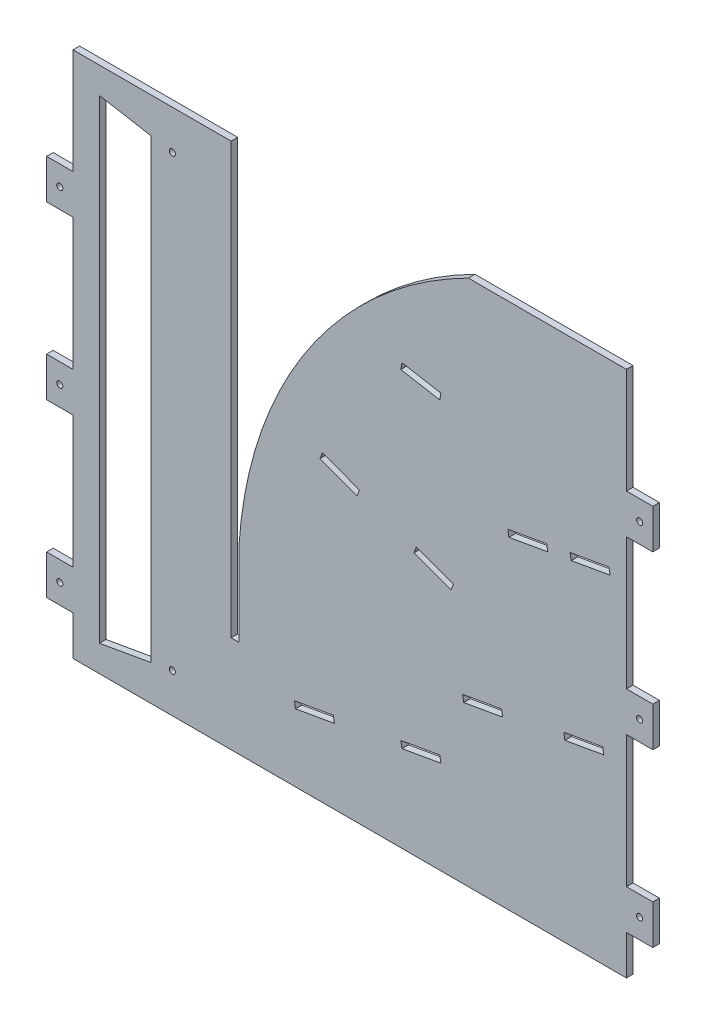
SolidWorks part; units mm, degrees
ref_plane "Front Plane" through (0, 0, 0) normal (0, 0, 1) x (1, 0, 0)
ref_plane "Top Plane" through (0, 0, 0) normal (0, 1, 0) x (1, 0, 0)
ref_plane "Right Plane" through (0, 0, 0) normal (1, 0, 0) x (0, 0, -1)
sketch "Sketch1" plane through (0, 0, 0) normal (0, 0, 1) x (1, 0, 0)
  line L0 (76.2, 254) -> (76.2, 46.7342)
  line L1 (190.5, 55.2817) -> (190.5, 254) construction
  line L2 (0, 0) -> (0, 19.05)
  line L3 (0, 254) -> (76.2, 254)
  line L5 (0, 203.2) -> (0, 254)
  line L6 (190.5, 254) -> (266.7, 254)
  line L7 (266.7, 254) -> (266.7, 203.2)
  line L8 (266.7, 0) -> (0, 0)
  line L9 (266.7, 203.2) -> (279.4, 203.2)
  line L10 (279.4, 203.2) -> (279.4, 184.15)
  line L11 (279.4, 184.15) -> (266.7, 184.15)
  line L12 (266.7, 184.15) -> (266.7, 120.65)
  line L13 (266.7, 120.65) -> (279.4, 120.65)
  line L14 (279.4, 120.65) -> (279.4, 101.6)
  line L15 (279.4, 101.6) -> (266.7, 101.6)
  line L16 (0, 203.2) -> (-12.7, 203.2)
  line L17 (0, 120.65) -> (0, 184.15)
  line L18 (0, 184.15) -> (-12.7, 184.15)
  line L19 (-12.7, 203.2) -> (-12.7, 184.15)
  line L20 (0, 120.65) -> (-12.7, 120.65)
  line L21 (0, 38.1) -> (0, 101.6)
  line L22 (0, 101.6) -> (-12.7, 101.6)
  line L23 (-12.7, 120.65) -> (-12.7, 101.6)
  line L24 (0, 38.1) -> (-12.7, 38.1)
  line L25 (266.7, 101.6) -> (266.7, 38.1)
  line L26 (0, 19.05) -> (-12.7, 19.05)
  line L27 (-12.7, 38.1) -> (-12.7, 19.05)
  line L28 (266.7, 38.1) -> (279.4, 38.1)
  line L29 (279.4, 38.1) -> (279.4, 19.05)
  line L30 (279.4, 19.05) -> (266.7, 19.05)
  line L31 (266.7, 19.05) -> (266.7, 0)
  line L33 (76.2, 46.7342) -> (80.01, 46.7342)
  line L34 (80.01, 46.7342) -> (80.01, 87.375)
  arc A0 (80.01, 87.375) -> (190.5, 254) centre (281.0737, 73.9943) cw
  dimension "D5" = 19.05
  dimension "D7" = 3.81
  dimension "D1" = 254
  dimension "D2" = 76.2
  dimension "D3" = 12.7
  dimension "D4" = 19.05
  dimension "D6" = 266.7
  dimension "D13" = 63.5
  dimension "D14" = 63.5
extrude "Boss-Extrude1" add sketch "Sketch1" along normal blind 3.175
sketch "Sketch4" [suppressed] plane through (0, 0, 3.175) normal (0, 0, 1) x (1, 0, 0)
  text T0 "Gravity Gizmo" font "Century Gothic" height in points 48
sketch "Sketch10" plane through (0, 0, 3.175) normal (0, 0, 1) x (1, 0, 0)
  line L0 (12.7, 12.7) -> (12.7, 241.3)
  line L1 (12.7, 12.7) -> (37.7141, 17.1107)
  line L2 (12.7, 241.3) -> (37.7141, 236.8893)
  line L3 (37.7141, 17.1107) -> (37.7141, 236.8893)
  line L4 (0, 19.05) -> (0, 0) construction
  line L5 (0, 0) -> (266.7, 0) construction
  line L6 (76.2, 254) -> (0, 254) construction
  point P3 (133.35, 0)
  dimension "D1" = 25.4
  dimension "D2" = 12.7
  dimension "D3" = 280
  dimension "D4" = 12.7
  dimension "D5" = 12.7
  dimension "D6" = 280
extrude "Cut-Extrude5" cut sketch "Sketch10" against normal through all
hole_wizard "#4 Clearance Hole1" positions "Sketch17" profile "Sketch16" hole size "#4" standard "ANSI Inch" end condition through all
sketch "Sketch17" plane through (0, 0, 3.175) normal (0, 0, 1) x (1, 0, 0)
  line L0 (-12.7, 184.15) -> (0, 184.15) construction
  line L4 (-12.7, 101.6) -> (0, 101.6) construction
  line L6 (-12.7, 19.05) -> (0, 19.05) construction
  line L12 (0, 101.6) -> (0, 38.1) construction
  line L13 (0, 184.15) -> (0, 120.65) construction
  line L14 (0, 254) -> (0, 203.2) construction
  line L15 (266.7, 19.05) -> (279.4, 19.05) construction
  line L16 (266.7, 101.6) -> (279.4, 101.6) construction
  line L17 (266.7, 184.15) -> (279.4, 184.15) construction
  line L18 (266.7, 203.2) -> (266.7, 254) construction
  line L19 (266.7, 120.65) -> (266.7, 184.15) construction
  line L20 (266.7, 38.1) -> (266.7, 101.6) construction
  line L21 (12.7, 241.3) -> (37.7141, 236.8893) construction
  line L22 (12.7, 12.7) -> (37.7141, 17.1107) construction
  line L23 (12.7, 241.3) -> (37.7141, 236.8893) construction
  line L24 (12.7, 12.7) -> (37.7141, 17.1107) construction
  line L26 (12.7, 241.3) -> (57.1853, 233.456) construction
  line L28 (12.7, 12.7) -> (77.3136, 24.0931) construction
  line L30 (37.7141, 17.1107) -> (37.7141, 236.8893) construction
  point P0 (-6.35, 193.675)
  point P2 (-6.35, 111.125)
  point P4 (-6.35, 28.575)
  point P56 (273.05, 193.675)
  point P58 (273.05, 111.125)
  point P60 (273.05, 28.575)
  point P87 (47.8741, 235.0979)
  point P95 (47.8741, 18.9021)
  dimension "D1" = 9.525
  dimension "D2" = 6.35
  dimension "D3" = 9.525
  dimension "D4" = 9.525
  dimension "D5" = 9.525
  dimension "D6" = 6.35
  dimension "D7" = 9.525
  dimension "D8" = 6.35
  dimension "D9" = 9.525
  dimension "D10" = 6.35
  dimension "D11" = 6.35
  dimension "D12" = 6.35
  dimension "D13" = 10.16
  dimension "D14" = 10.16
sketch "Sketch16" plane through (-6.35, 193.675, 3.175) normal (1, 0, 0) x (0, -1, 0)
  line L0 (0, 0) -> (0, 3.175)
  line L1 (0, 3.175) -> (1.4732, 3.175)
  line L2 (1.4732, 3.175) -> (1.4732, 0)
  line L5 (1.4732, 0) -> (0, 0)
  line L11 (0, -6.35) -> (0, 107.95) construction
  dimension "Thru Hole Dia." = 2.9464
  dimension "Thru Hole Depth" = 3.175
sketch "Sketch21" plane through (0, 0, 3.175) normal (0, 0, 1) x (1, 0, 0)
  line L0 (12.7, 12.7) -> (37.7141, 17.1107) construction
  line L1 (12.7, 241.3) -> (37.7141, 236.8893) construction
  line L2 (12.7, 12.7) -> (37.7141, 17.1107) construction
  line L3 (12.7, 241.3) -> (37.7141, 236.8893) construction
  line L4 (12.7, 241.3) -> (240.5132, 201.1304) construction
  line L5 (18.724, 227.3419) -> (205.5657, 194.3966) construction
  line L6 (21.9553, 20.7799) -> (207.6201, 53.5176) construction
  line L7 (257.4976, 91.1808) -> (181.8916, 77.8494) construction
  line L9 (267.1952, 168.876) -> (217.3231, 160.0823) construction
  line L11 (116.3001, 147.3576) -> (202.1524, 115.6496) construction
  line L15 (158.5262, 202.691) -> (157.9748, 199.5642)
  line L16 (157.9748, 199.5642) -> (176.7354, 196.2562)
  line L17 (176.7354, 196.2562) -> (177.2867, 199.383)
  line L18 (177.2867, 199.383) -> (158.5262, 202.691)
  line L19 (239.5224, 163.9966) -> (240.0738, 160.8698)
  line L20 (240.0738, 160.8698) -> (258.8344, 164.1778)
  line L21 (258.8344, 164.1778) -> (258.283, 167.3046)
  line L22 (258.283, 167.3046) -> (239.5224, 163.9966)
  line L23 (120.1678, 145.9291) -> (119.0678, 142.9507)
  line L24 (119.0678, 142.9507) -> (136.938, 136.3507)
  line L25 (136.938, 136.3507) -> (138.038, 139.3291)
  line L26 (138.038, 139.3291) -> (120.1678, 145.9291)
  line L27 (165.4389, 129.2091) -> (164.3389, 126.2307)
  line L28 (164.3389, 126.2307) -> (182.209, 119.6307)
  line L29 (182.209, 119.6307) -> (183.309, 122.6091)
  line L30 (183.309, 122.6091) -> (165.4389, 129.2091)
  line L31 (236.4922, 87.4769) -> (237.0435, 84.3502)
  line L32 (237.0435, 84.3502) -> (255.8041, 87.6582)
  line L33 (255.8041, 87.6582) -> (255.2528, 90.7849)
  line L34 (187.7146, 78.8761) -> (188.266, 75.7494)
  line L35 (188.266, 75.7494) -> (207.0266, 79.0574)
  line L36 (207.0266, 79.0574) -> (206.4752, 82.1841)
  line L37 (228.2661, 162.0118) -> (228.8174, 158.885)
  line L38 (228.8174, 158.885) -> (210.0568, 155.577)
  line L39 (210.0568, 155.577) -> (209.5055, 158.7038)
  line L40 (106.6959, 35.722) -> (107.2472, 32.5952)
  line L41 (107.2472, 32.5952) -> (126.0078, 35.9032)
  line L42 (126.0078, 35.9032) -> (125.4565, 39.03)
  line L43 (125.4565, 39.03) -> (106.6959, 35.722)
  line L44 (157.9748, 44.7638) -> (158.5262, 41.6371)
  line L45 (158.5262, 41.6371) -> (177.2867, 44.9451)
  line L46 (177.2867, 44.9451) -> (176.7354, 48.0718)
  line L47 (236.4922, 87.4769) -> (255.2528, 90.7849)
  line L48 (206.4752, 82.1841) -> (187.7146, 78.8761)
  line L49 (209.5055, 158.7038) -> (228.2661, 162.0118)
  line L51 (157.9748, 44.7638) -> (176.7354, 48.0718)
  dimension "D1" = 12.7
  dimension "D2" = 6.35
  dimension "D6" = 3.175
  dimension "D7" = 19.05
  dimension "D9" = 3.175
  dimension "D10" = 19.05
  dimension "D11" = 29.21
  dimension "D12" = 30.48
  dimension "D13" = 33.02
  dimension "D14" = 11.43
extrude "Cut-Extrude15" cut sketch "Sketch21" against normal through all
